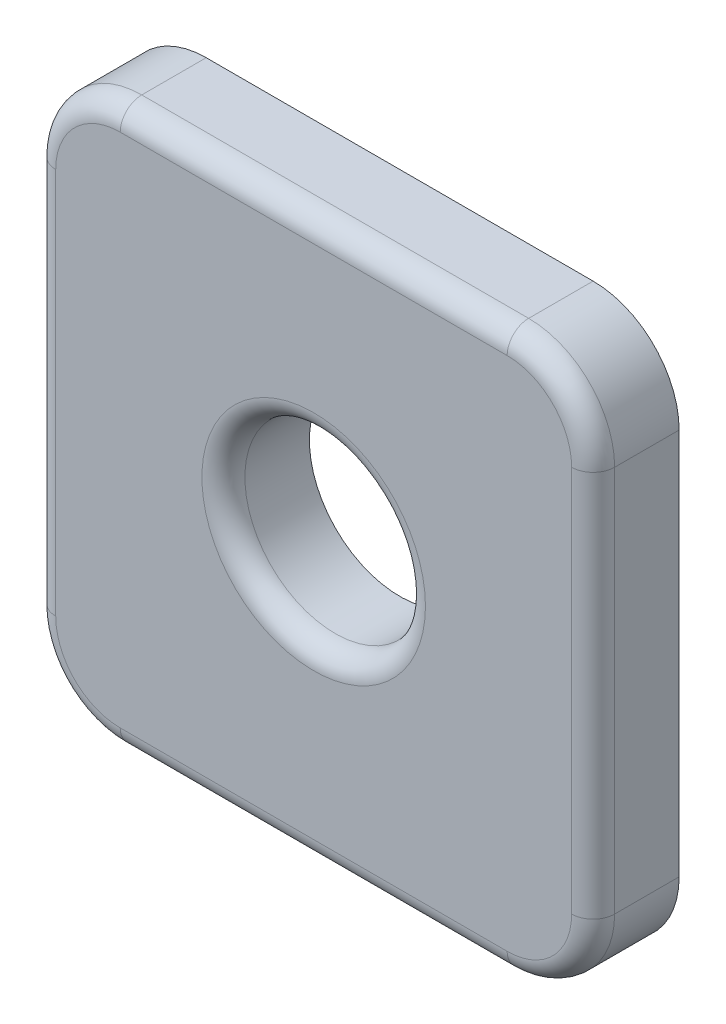
SolidWorks part; units mm, degrees
ref_plane "Plan de face" through (0, 0, 0) normal (0, 0, 1) x (1, 0, 0)
ref_plane "Plan de dessus" through (0, 0, 0) normal (0, 1, 0) x (1, 0, 0)
ref_plane "Plan de droite" through (0, 0, 0) normal (1, 0, 0) x (0, 0, -1)
sketch "Esquisse1" plane through (0, 0, 0) normal (0, 0, 1) x (1, 0, 0)
  line L1 (-11.5356, 8.7893) -> (1.4644, 8.7893)
  line L2 (-11.5356, 8.7893) -> (-11.5356, -4.2107)
  line L3 (-11.5356, -4.2107) -> (1.4644, -4.2107)
  line L4 (1.4644, 8.7893) -> (1.4644, -4.2107)
  line L5 (-11.5356, 8.7893) -> (1.4644, -4.2107) construction
  line L6 (-11.5356, -4.2107) -> (1.4644, 8.7893) construction
  circle A0 centre (-5.0356, 2.2893) radius 2.1
  dimension "D3" = 4.2
  dimension "D1" = 13
  dimension "D2" = 13
extrude "Boss.-Extru.1" add sketch "Esquisse1" along normal blind 2
fillet "Congé1" radius 2 4 edges at (-11.5356, -4.2107, 1) (1.4644, -4.2107, 1) (-11.5356, 8.7893, 1) (1.4644, 8.7893, 1)
fillet "Congé2" radius 0.5 9 edges at (-2.9356, 2.2893, 2) (-10.9498, 8.2035, 2) (-5.0356, 8.7893, 2) (0.8786, 8.2035, 2) (1.4644, 2.2893, 2) (0.8786, -3.6249, 2) (-5.0356, -4.2107, 2) (-10.9498, -3.6249, 2) (-11.5356, 2.2893, 2)
